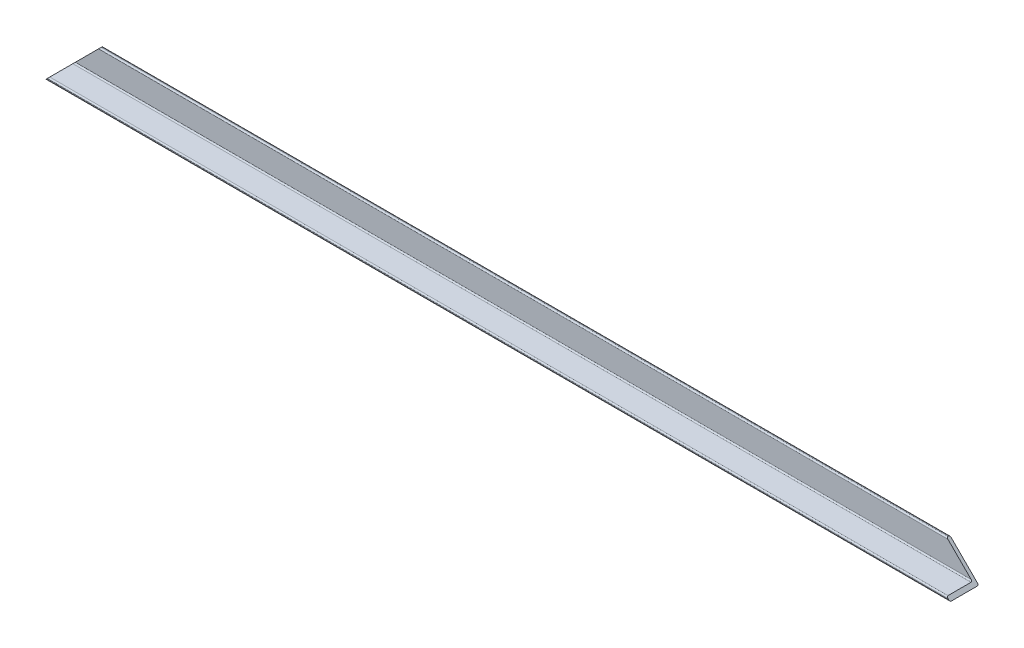
SolidWorks part; units mm, degrees
ref_plane "Front Plane" through (0, 0, 0) normal (0, 0, 1) x (1, 0, 0)
ref_plane "Top Plane" through (0, 0, 0) normal (0, 1, 0) x (1, 0, 0)
ref_plane "Right Plane" through (0, 0, 0) normal (1, 0, 0) x (0, 0, -1)
sketch "Sketch1" plane through (0, 0, 0) normal (0, 1, 0) x (1, 0, 0)
  line L1 (-360, 11.25) -> (360, 11.25)
  line L2 (-360, 11.25) -> (-360, -11.25)
  line L3 (-360, -11.25) -> (360, -11.25)
  line L4 (360, 11.25) -> (360, -11.25)
  line L5 (-360, 11.25) -> (360, -11.25) construction
  line L6 (-360, -11.25) -> (360, 11.25) construction
  point P0 (0, 0)
  dimension "D1" = 720
  dimension "D2" = 22.5
extrude "Boss-Extrude1" add sketch "Sketch1" along normal blind 2.5
sketch "Sketch2" plane through (0, 2.5, 0) normal (0, 1, 0) x (1, 0, 0)
  line L0 (360, -11.25) -> (360, 11.25) construction
  line L1 (-360, 11.25) -> (360, 11.25)
  line L2 (-360, 11.25) -> (-360, 8.75)
  line L3 (-360, 8.75) -> (360, 8.75)
  line L4 (360, 11.25) -> (360, 8.75)
  dimension "D1" = 2.5
extrude "Boss-Extrude2" add sketch "Sketch2" along normal blind 20
sketch "Sketch3" plane through (0, 0, -8.75) normal (0, 0, 1) x (1, 0, 0)
  line L0 (-360, 22.5) -> (-360, -7.5)
  line L1 (-360, 22.5) -> (360, 22.5) construction
  line L2 (-360, -7.5) -> (-330, 22.5)
  line L3 (-330, 22.5) -> (-360, 22.5)
  line L4 (360, 22.5) -> (360, -7.5)
  line L5 (360, -7.5) -> (330, 22.5)
  line L6 (330, 22.5) -> (360, 22.5)
  dimension "D1" = 45
  dimension "D2" = 30
  dimension "D3" = 30
  dimension "D4" = 45
extrude "Cut-Extrude1" cut sketch "Sketch3" against normal blind 25 and the other way through all
fillet "Fillet2" radius 1 6 edges at (0, 0, -11.25) (0, 0, 11.25) (0, 2.5, 11.25) (0, 22.5, -11.25) (0, 22.5, -8.75) (0, 2.5, -8.75)
